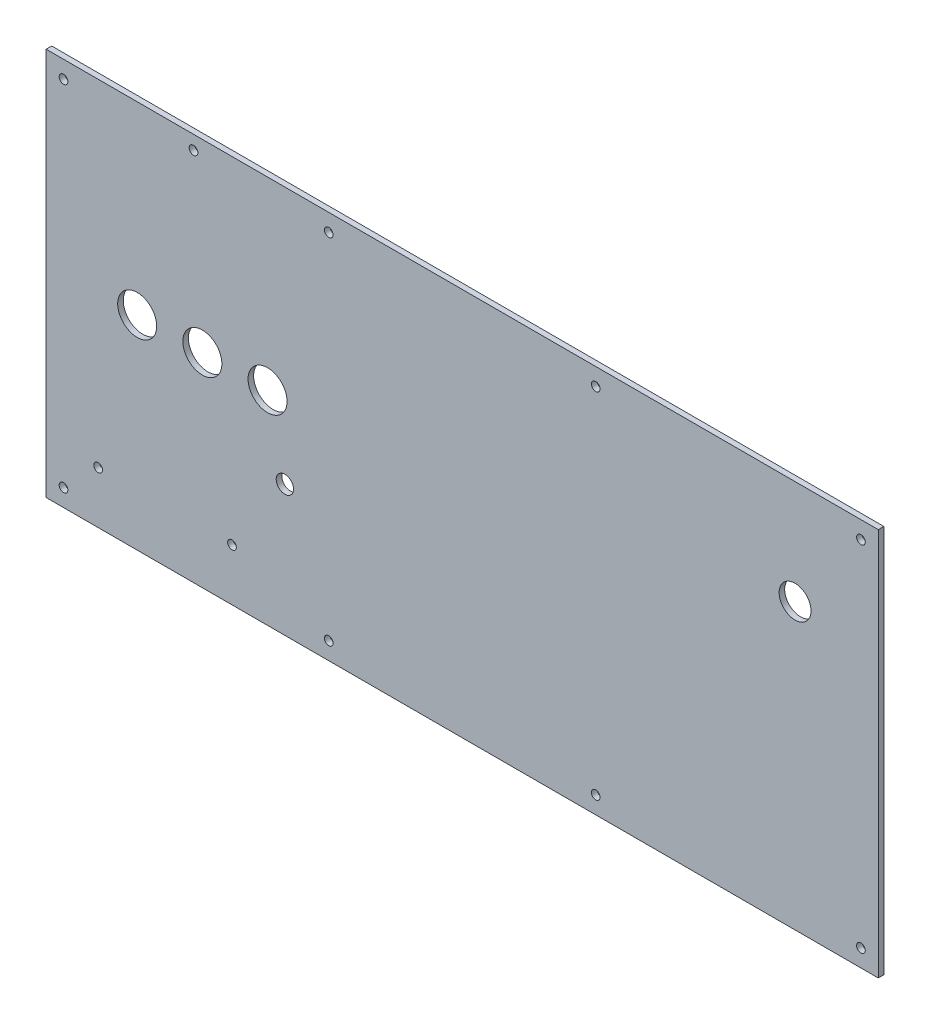
SolidWorks part; units mm, degrees
material "Acrylic (Medium-high impact)"
ref_plane "Front Plane" through (0, 0, 0) normal (0, 0, 1) x (1, 0, 0)
ref_plane "Top Plane" through (0, 0, 0) normal (0, 1, 0) x (1, 0, 0)
ref_plane "Right Plane" through (0, 0, 0) normal (1, 0, 0) x (0, 0, -1)
sketch "Sketch1" plane through (0, 0, 0) normal (0, 0, 1) x (1, 0, 0)
  line L1 (-97.155, 142.24) -> (207.645, 142.24)
  line L2 (-97.155, 142.24) -> (-97.155, 0)
  line L3 (-97.155, 0) -> (207.645, 0)
  line L4 (207.645, 142.24) -> (207.645, 0)
extrude "Extrude1" add sketch "Sketch1" along normal blind 2.032
sketch "Sketch3" plane through (0, 0, 2.032) normal (0, 0, 1) x (1, 0, 0)
  line L0 (-90.805, -9.4597) -> (-90.805, 127.5192) construction
  line L1 (-97.155, 129.794) -> (-84.455, 129.794) construction
  line L2 (55.245, 142.24) -> (55.245, 320.3404) construction
  line L3 (6.35, -13.5569) -> (6.35, 321.8506) construction
  line L4 (12.7, 142.24) -> (12.7, 215.9) construction
  line L5 (0, 142.24) -> (0, 215.9) construction
  line L6 (-71.755, 6.35) -> (-50.2069, 6.35) construction
  line L8 (-84.455, 0) -> (-84.455, 12.7) construction
  line L11 (-97.155, 135.89) -> (207.645, 135.89)
  line L12 (-97.155, 135.89) -> (182.245, 135.89) construction
  circle A0 centre (-90.805, 135.89) radius 1.5875
  circle A1 centre (-90.805, 6.35) radius 1.5875
  circle A2 centre (6.35, 135.89) radius 1.5875
  circle A3 centre (6.35, 6.35) radius 1.5875
  circle A4 centre (104.14, 6.35) radius 1.5875
  circle A5 centre (104.14, 135.89) radius 1.5875
  circle A6 centre (201.295, 6.35) radius 1.5875
  circle A7 centre (201.295, 135.89) radius 1.5875
  point P2 (-90.805, 129.794)
  point P18 (-84.455, 6.35)
  point P40 (201.295, 129.794)
  dimension "D2" = 3.175
  dimension "D1" = 6.35
extrude "Cut-Extrude1" cut sketch "Sketch3" against normal through all
sketch "Sketch4" plane through (0, 0, 2.032) normal (0, 0, 1) x (1, 0, 0)
  line L0 (207.645, 142.24) -> (-97.155, 142.24) construction
  line L1 (-84.455, 142.24) -> (0, 142.24) construction
  line L2 (-84.455, 142.24) -> (-84.455, 12.7) construction
  line L3 (-84.455, 12.7) -> (0, 12.7) construction
  line L4 (0, 142.24) -> (0, 12.7) construction
  line L5 (-97.155, 142.24) -> (-97.155, 0) construction
  line L6 (-97.155, 0) -> (207.645, 0) construction
  line L7 (-84.455, 139.7) -> (0, 139.7) construction
  line L8 (207.645, 0) -> (207.645, 142.24) construction
  circle A0 centre (6.35, 6.35) radius 1.5875 construction
  circle A1 centre (-63.8175, 74.6125) radius 7.1437
  circle A2 centre (-39.9415, 74.6125) radius 7.1437
  circle A3 centre (-16.0655, 74.6125) radius 7.1438
  circle A4 centre (-43.18, 137.16) radius 1.5875
  circle A5 centre (-9.7155, 47.9425) radius 3.175
  circle A6 centre (-78.105, 19.05) radius 1.5875
  circle A7 centre (-29.083, 19.05) radius 1.5875
  circle A8 centre (177.165, 104.14) radius 5.842
  dimension "D5" = 14.2875
  dimension "D8" = 3.175
  dimension "D11" = 26.67
  dimension "D13" = 6.35
  dimension "D16" = 3.175
  dimension "D18" = 11.684
  dimension "D1" = 12.7
  dimension "D2" = 12.7
  dimension "D3" = 6.35
  dimension "D4" = 20.6375
  dimension "D6" = 61.9125
  dimension "D7" = 2.54
  dimension "D9" = 5.08
  dimension "D10" = 41.275
  dimension "D12" = 6.35
  dimension "D14" = 6.35
  dimension "D15" = 6.35
  dimension "D17" = 49.022
  dimension "D19" = 30.48
  dimension "D20" = 38.1
extrude "Extrude2" cut sketch "Sketch4" against normal through all
